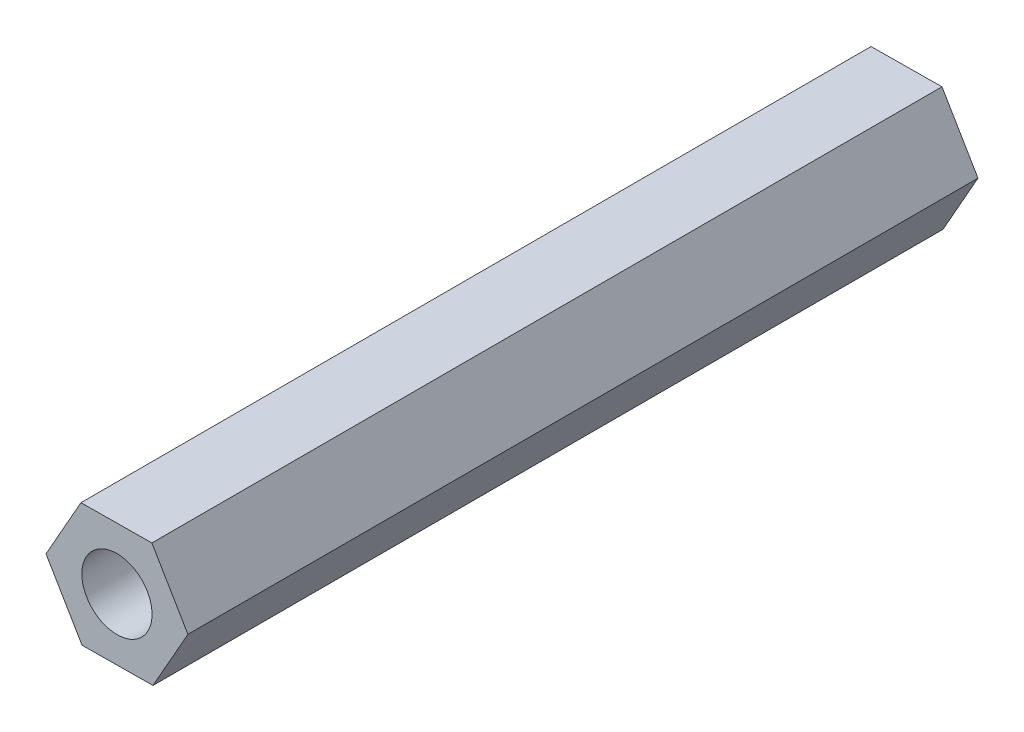
SolidWorks part; units mm, degrees
ref_plane "前视基准面" through (0, 0, 0) normal (0, 0, 1) x (1, 0, 0)
ref_plane "上视基准面" through (0, 0, 0) normal (0, 1, 0) x (1, 0, 0)
ref_plane "右视基准面" through (0, 0, 0) normal (1, 0, 0) x (0, 0, -1)
sketch "草图1" plane through (0, 0, 0) normal (0, 0, 1) x (1, 0, 0)
  line L1 (2.0515, -3.4821) -> (4.0413, 0.0356)
  line L2 (4.0413, 0.0356) -> (1.9898, 3.5177)
  line L3 (1.9898, 3.5177) -> (-2.0515, 3.4821)
  line L4 (-2.0515, 3.4821) -> (-4.0413, -0.0356)
  line L5 (-4.0413, -0.0356) -> (-1.9898, -3.5177)
  line L6 (-1.9898, -3.5177) -> (2.0515, -3.4821)
  circle A0 centre (0, 0) radius 3.5 construction
  circle A1 centre (0, 0) radius 2
extrude "凸台-拉伸1" add sketch "草图1" along normal blind 45
